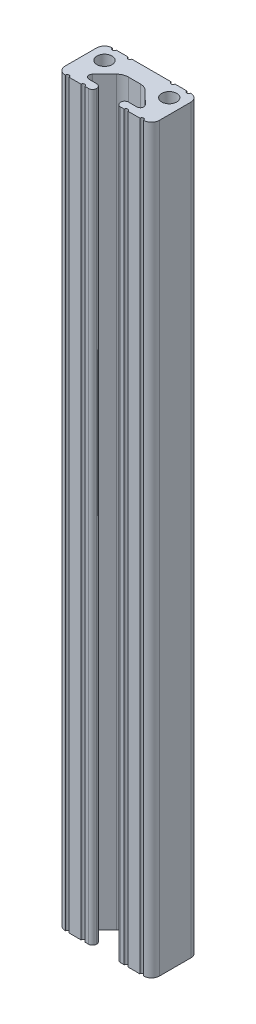
SolidWorks part; units mm, degrees
material "6061-T6 (SS)"
ref_plane "Front" through (0, 0, 0) normal (0, 0, 1) x (1, 0, 0)
ref_plane "Top" through (0, 0, 0) normal (0, 1, 0) x (1, 0, 0)
ref_plane "Right" through (0, 0, 0) normal (1, 0, 0) x (0, 0, -1)
sketch "Sketch1" plane through (0, 0, 0) normal (0, 0, 1) x (1, 0, 0)
  line L0 (0, 100) -> (0, -100)
  dimension "D1" = 200
other "10 1050 PROFILE(1)"
ref_plane "Plane1" through (0, 100, 0) normal (0, -1, 0) x (1, 0, 0)
sketch "Sketch18" plane through (0, 100, 0) normal (0, -1, 0) x (1, 0, 0)
  line L1 (12.7, -6.35) -> (-12.7, -6.35) construction
  line L2 (12.7, -6.35) -> (12.7, 6.35) construction
  line L3 (12.7, 6.35) -> (-12.7, 6.35) construction
  line L4 (-12.7, -6.35) -> (-12.7, 6.35) construction
  line L5 (12.7, -6.35) -> (-12.7, 6.35) construction
  line L6 (12.7, 6.35) -> (-12.7, -6.35) construction
  line L38 (9.5511, 6.35) -> (6.331, 6.35)
  line L39 (5.3178, 6.35) -> (4.2875, 6.35)
  line L40 (3.2385, 5.301) -> (3.2385, 5.1892)
  line L41 (4.2875, 4.1402) -> (6.5413, 4.1402)
  line L42 (7.2007, 2.5462) -> (3.8745, -0.7739)
  line L43 (1.6315, -1.7018) -> (-1.6315, -1.7018)
  line L44 (-3.8745, -0.7739) -> (-7.0916, 2.4373)
  line L45 (-6.3872, 4.1402) -> (-4.2875, 4.1402)
  line L46 (-3.2385, 5.1892) -> (-3.2385, 5.301)
  line L47 (-4.2875, 6.35) -> (-5.3192, 6.35)
  line L48 (-6.3324, 6.35) -> (-9.5525, 6.35)
  line L49 (-10.5657, 6.3457) -> (-10.5913, 6.3457)
  line L50 (-12.7, 4.2373) -> (-12.7, -4.2331)
  line L51 (-9.5516, -6.35) -> (-6.323, -6.35)
  line L52 (-5.31, -6.35) -> (5.31, -6.35)
  line L53 (6.323, -6.35) -> (9.5502, -6.35)
  line L54 (10.5633, -6.3403) -> (10.5899, -6.3405)
  line L55 (12.7, -4.2321) -> (12.7, 4.2447)
  line L56 (10.591, 6.3531) -> (10.5643, 6.3531)
  circle A1 centre (-8.7376, -2.3876) radius 2.032
  circle A3 centre (8.7376, -2.3876) radius 2.032
  arc A40 (9.5511, 6.35) -> (10.5643, 6.3531) centre (10.0577, 6.35) ccw
  arc A41 (5.3178, 6.35) -> (6.331, 6.35) centre (5.8244, 6.35) ccw
  arc A42 (4.2875, 6.35) -> (3.2385, 5.301) centre (4.2875, 5.301) ccw
  arc A43 (3.2385, 5.1892) -> (4.2875, 4.1402) centre (4.2875, 5.1892) ccw
  arc A44 (7.2007, 2.5462) -> (6.5413, 4.1402) centre (6.5413, 3.2068) ccw
  arc A45 (1.6315, -1.7018) -> (3.8745, -0.7739) centre (1.6315, 1.4732) ccw
  arc A46 (-3.8745, -0.7739) -> (-1.6315, -1.7018) centre (-1.6315, 1.4732) ccw
  arc A47 (-6.3872, 4.1402) -> (-7.0916, 2.4373) centre (-6.3872, 3.1431) ccw
  arc A48 (-4.2875, 4.1402) -> (-3.2385, 5.1892) centre (-4.2875, 5.1892) ccw
  arc A49 (-3.2385, 5.301) -> (-4.2875, 6.35) centre (-4.2875, 5.301) ccw
  arc A50 (-6.3324, 6.35) -> (-5.3192, 6.35) centre (-5.8258, 6.35) ccw
  arc A51 (-10.5657, 6.3457) -> (-9.5525, 6.35) centre (-10.0591, 6.35) ccw
  arc A52 (-10.5913, 6.3457) -> (-12.7, 4.2373) centre (-10.5916, 4.2373) ccw
  arc A53 (-12.7, -4.2331) -> (-10.5647, -6.3413) centre (-10.5916, -4.2331) ccw
  arc A54 (-9.5516, -6.35) -> (-10.5647, -6.3413) centre (-10.0581, -6.3412) ccw
  arc A55 (-5.31, -6.35) -> (-6.323, -6.35) centre (-5.8165, -6.3412) ccw
  arc A56 (6.323, -6.35) -> (5.31, -6.35) centre (5.8165, -6.3412) ccw
  arc A57 (10.5633, -6.3403) -> (9.5502, -6.35) centre (10.0567, -6.3412) ccw
  arc A58 (10.5899, -6.3405) -> (12.7, -4.2321) centre (10.5916, -4.2321) ccw
  arc A59 (12.7, 4.2447) -> (10.591, 6.3531) centre (10.5916, 4.2447) ccw
  point P3 (0, 0)
  point P26 (0, 6.35)
  point P29 (0, -6.35)
  point P33 (-12.7, 6.35)
  point P36 (-12.7, -6.35)
  point P38 (12.7, 6.35)
  point P41 (12.7, -6.35)
  point P44 (0, 0)
  dimension "D1" = 12.7
  dimension "D2" = 25.4
